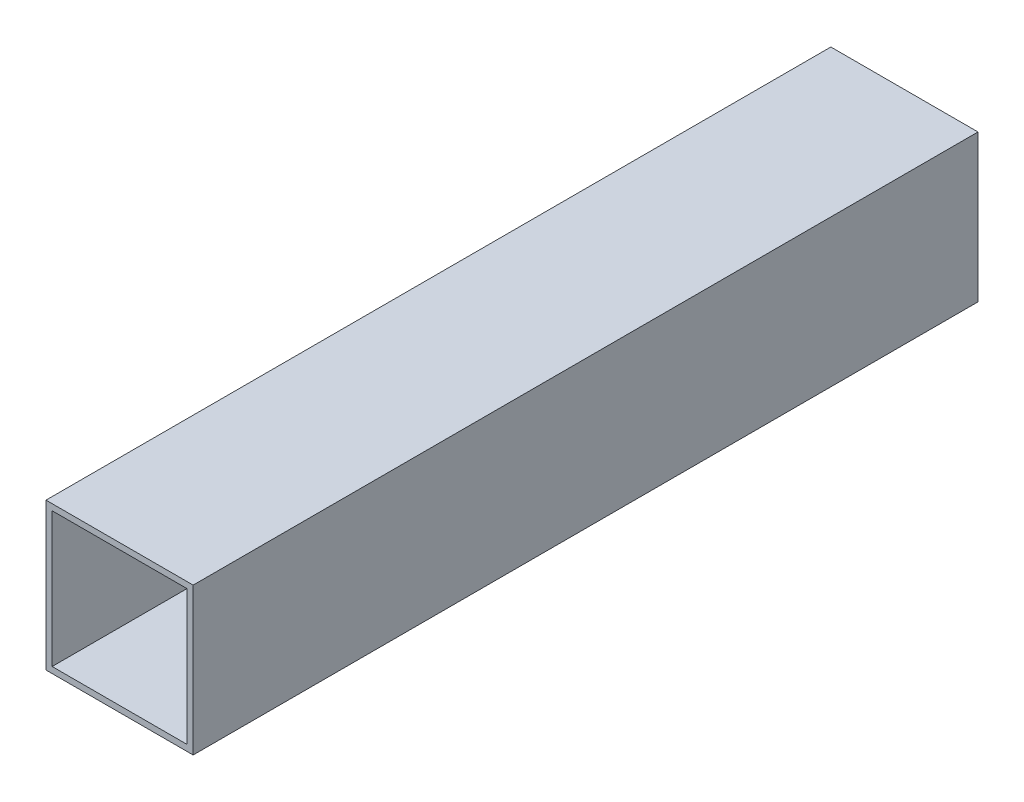
SolidWorks part; units mm, degrees
material "6061-T6 (SS)"
ref_plane "Front Plane" through (0, 0, 0) normal (0, 0, 1) x (1, 0, 0)
ref_plane "Top Plane" through (0, 0, 0) normal (0, 1, 0) x (1, 0, 0)
ref_plane "Right Plane" through (0, 0, 0) normal (1, 0, 0) x (0, 0, -1)
sketch "Sketch2" plane through (0, 0, 0) normal (0, 0, 1) x (1, 0, 0)
  line L0 (0, 19.05) -> (1.5875, 19.05) construction
  line L1 (0, 0) -> (38.1, 0)
  line L2 (0, 0) -> (0, 38.1)
  line L3 (0, 38.1) -> (38.1, 38.1)
  line L4 (38.1, 0) -> (38.1, 38.1)
  line L5 (1.5875, 1.5875) -> (36.5125, 1.5875)
  line L6 (1.5875, 1.5875) -> (1.5875, 36.5125)
  line L7 (1.5875, 36.5125) -> (36.5125, 36.5125)
  line L8 (36.5125, 1.5875) -> (36.5125, 36.5125)
  line L9 (19.05, 36.5125) -> (19.05, 38.1) construction
  line L10 (36.5125, 19.05) -> (38.1, 19.05) construction
  line L11 (19.05, 0) -> (19.05, 1.5875) construction
  dimension "D1" = 38.1
  dimension "D2" = 1.5875
  dimension "D3" = 38.1
extrude "Boss-Extrude1" add sketch "Sketch2" along normal blind 203.2
